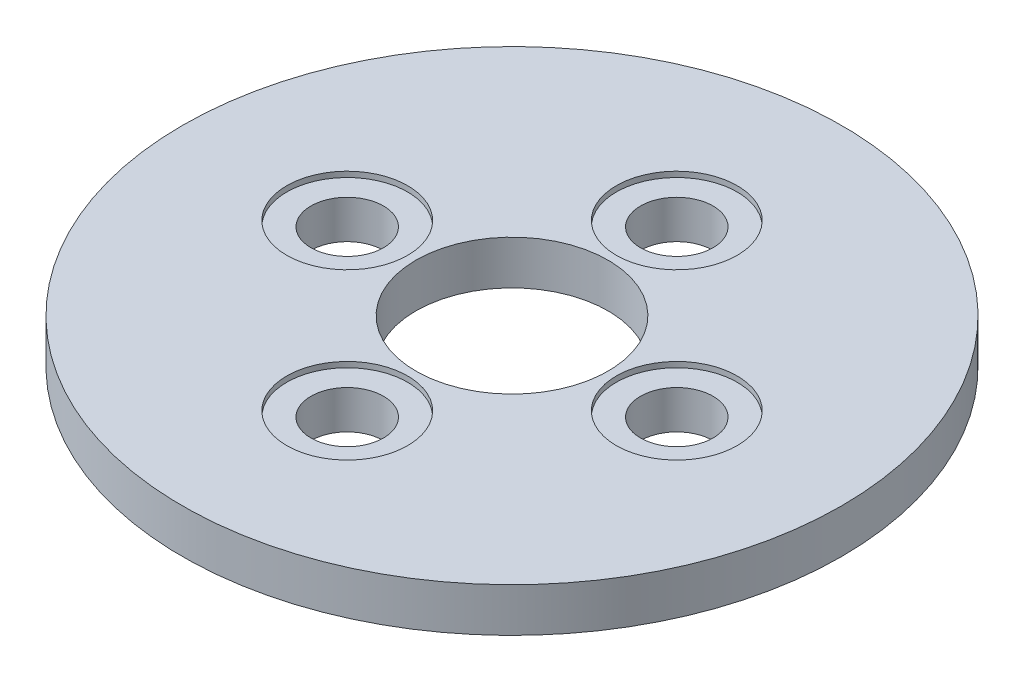
SolidWorks part; units mm, degrees
ref_plane "前视基准面" through (0, 0, 0) normal (0, 0, 1) x (1, 0, 0)
ref_plane "上视基准面" through (0, 0, 0) normal (0, 1, 0) x (1, 0, 0)
ref_plane "右视基准面" through (0, 0, 0) normal (1, 0, 0) x (0, 0, -1)
sketch "草图1" plane through (0, 0, 0) normal (0, 0, 1) x (1, 0, 0)
  line L6 (0, 0) -> (8.75, 0) construction
  line L7 (8.75, 0) -> (8.75, 4) construction
  line L8 (8.75, 4) -> (0, 4) construction
  line L9 (0, 4) -> (0, 0) construction
  line L10 (8.75, 0) -> (30, 0)
  line L12 (30, 0) -> (30, 4)
  line L14 (30, 4) -> (8.75, 4)
  line L15 (8.75, 4) -> (8.75, 0)
  point P2 (25, 0)
  point P9 (24.8373, 0)
  dimension "D1" = 8.75
  dimension "D2" = 30
  dimension "D4" = 4
revolve "旋转1" add sketch "草图1" angle 360 about L9
hole_wizard "M6 六角头螺栓的柱形沉头孔1" positions "草图4" profile "草图3" counterbore size "M6" standard "GB" end condition through all
sketch "草图4" plane through (0, 4, 0) normal (0, 1, 0) x (1, 0, 0)
  line L0 (-15, 0) -> (0, 0) construction
  line L1 (0, 0) -> (0, -15) construction
  line L3 (15, 0) -> (0, 0) construction
  line L4 (0, 0) -> (0, 15) construction
  point P2 (15, 0)
  point P4 (0, -15)
  point P12 (-15, 0)
  point P20 (0, 15)
  dimension "D1" = 15
sketch "草图3" plane through (15, 4, 0) normal (1, 0, 0) x (0, 0, 1)
  line L0 (0, 0) -> (0, 4)
  line L1 (0, 4) -> (3.3, 4)
  line L3 (3.3, 4) -> (3.3, 0.5)
  line L4 (3.3, 0.5) -> (5.5, 0.5)
  line L5 (5.5, 0.5) -> (5.5, 0)
  line L7 (5.5, 0) -> (0, 0)
  line L11 (0, -6.35) -> (0, 107.95) construction
  dimension "通孔孔直径" = 6.6
  dimension "通孔孔深度" = 4
  dimension "柱形沉头孔直径" = 11
  dimension "柱形沉头孔深度" = 0.5
